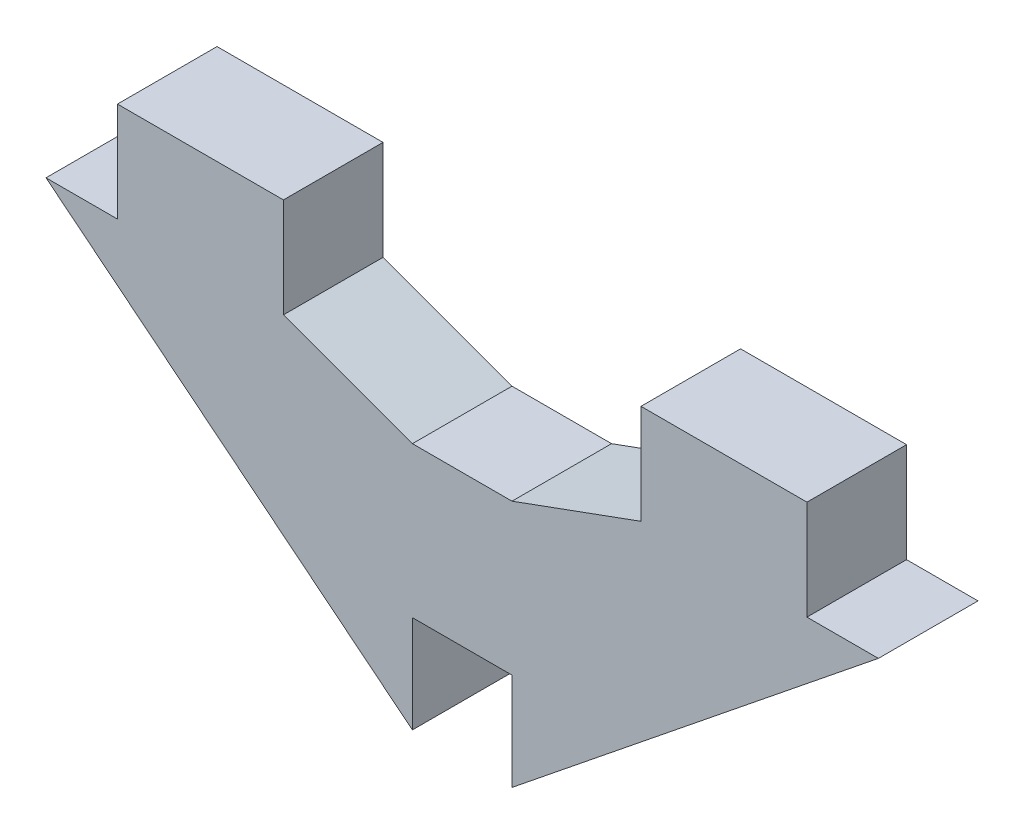
SolidWorks part; units mm, degrees
ref_plane "Front Plane" through (0, 0, 0) normal (0, 0, 1) x (1, 0, 0)
ref_plane "Top Plane" through (0, 0, 0) normal (0, 1, 0) x (1, 0, 0)
ref_plane "Right Plane" through (0, 0, 0) normal (1, 0, 0) x (0, 0, -1)
sketch "Sketch1" plane through (0, 0, 0) normal (0, 0, 1) x (1, 0, 0)
  line L0 (0, 54.2839) -> (1.524, 54.2839)
  line L1 (1.524, 54.2839) -> (0, 54.2839) construction
  line L2 (1.524, 54.2839) -> (1.524, 52.7953)
  line L3 (1.524, 52.7953) -> (7.1313, 57.3093)
  line L4 (7.1313, 57.3093) -> (6.0379, 57.3093)
  line L5 (6.0379, 57.3093) -> (6.0379, 58.8333)
  line L6 (6.0379, 58.8333) -> (3.4979, 58.8333)
  line L7 (3.4979, 58.8333) -> (3.4979, 57.3093)
  line L8 (0, 56.5893) -> (1.524, 56.5893)
  line L9 (1.524, 56.5893) -> (0, 56.5893) construction
  line L10 (1.524, 56.5893) -> (1.524, 54.2839) construction
  line L11 (1.524, 56.5893) -> (3.4979, 57.3093)
  line L12 (0.762, 54.2839) -> (0.762, 56.5893) construction
  line L13 (0, 56.5893) -> (-1.9739, 57.3093)
  line L14 (-1.9739, 58.8333) -> (-1.9739, 57.3093)
  line L15 (-4.5139, 58.8333) -> (-1.9739, 58.8333)
  line L16 (-4.5139, 57.3093) -> (-4.5139, 58.8333)
  line L17 (-5.6073, 57.3093) -> (-4.5139, 57.3093)
  line L18 (0, 52.7953) -> (-5.6073, 57.3093)
  line L19 (0, 54.2839) -> (0, 52.7953)
extrude "Boss-Extrude1" add sketch "Sketch1" along normal blind 1.524
